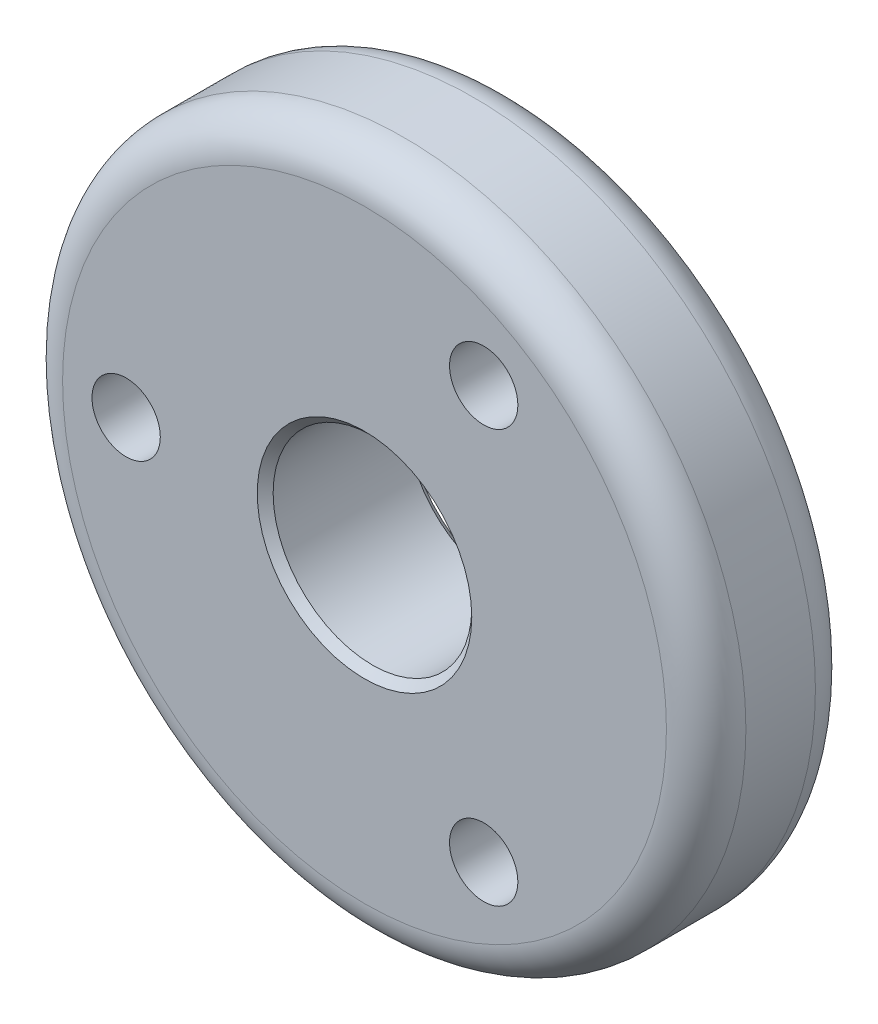
SolidWorks part; units mm, degrees
ref_plane "Front" through (0, 0, 0) normal (0, 0, 1) x (1, 0, 0)
ref_plane "Top" through (0, 0, 0) normal (0, 1, 0) x (1, 0, 0)
ref_plane "Right" through (0, 0, 0) normal (1, 0, 0) x (0, 0, -1)
sketch "Sketch1" plane through (0, 0, 0) normal (0, 0, 1) x (1, 0, 0)
  circle A0 centre (0, 0) radius 1.5875
  circle A1 centre (0, 0) radius 5.461
  dimension "D1" = 10.922
  dimension "D2" = 3.175
extrude "Boss-Extrude1" add sketch "Sketch1" along normal mid plane 2.3813
fillet "Fillet1" radius 0.635 2 edges at (5.461, 0, -1.1906) (5.461, 0, 1.1906)
chamfer "Chamfer1" distance 0.127 2 edges at (1.5875, 0, -1.1906) (1.5875, 0, 1.1906)
sketch "Sketch2" plane through (0, 0, 1.1906) normal (0, 0, 1) x (1, 0, 0)
  circle A0 centre (-3.81, 0) radius 0.5461
  point P2 (0, 0)
  point P4 (0, 0)
  dimension "D1" = 1.0922
  dimension "D2" = 3.81
extrude "Cut-Extrude1" cut sketch "Sketch2" against normal through all
pattern_circular "CirPattern1" count 3 over 360 about axis through (0, 0, 0) along (0, 0, 1) of "Cut-Extrude1"
